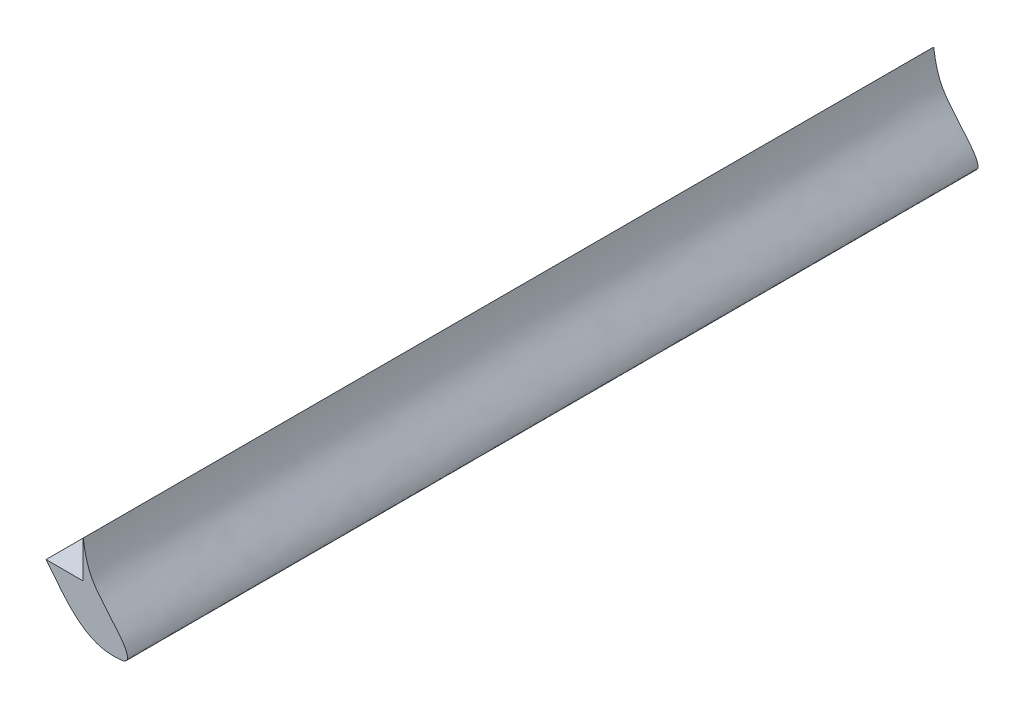
SolidWorks part; units mm, degrees
ref_plane "Front Plane" through (0, 0, 0) normal (0, 0, 1) x (1, 0, 0)
ref_plane "Top Plane" through (0, 0, 0) normal (0, 1, 0) x (1, 0, 0)
ref_plane "Right Plane" through (0, 0, 0) normal (1, 0, 0) x (0, 0, -1)
sketch "Sketch2" plane through (0, 0, 0) normal (0, 0, 1) x (1, 0, 0)
  line L0 (0, 0) -> (0, 3)
  line L1 (0, 0) -> (-3, 0)
  spline S0 degree 3 poles (-3, 0) (-1.9278, -1.3007) (-0.3217, -3.7558) (2.217, -4.0622) (2.8136, -4) knots 0 0 0 0 0.755605 1 1 1 1
  spline S1 degree 3 poles (2.8136, -4) (4.2826, -4.0206) (1.4412, -0.3099) (0.3385, 0.433) (0, 3) knots 0 0 0 0 0.345395 1 1 1 1
extrude "Boss-Extrude1" add sketch "Sketch2" against normal blind 68.58
